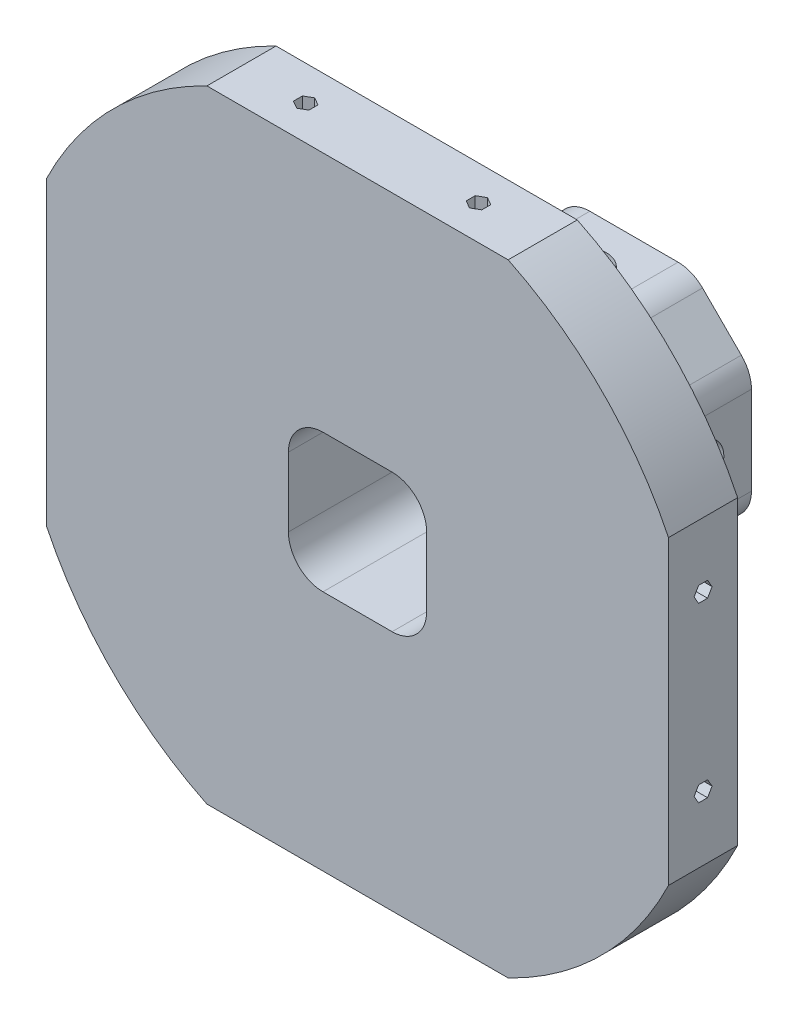
SolidWorks part; units mm, degrees
ref_plane "正面" through (0, 0, 0) normal (0, 0, 1) x (1, 0, 0)
ref_plane "平面" through (0, 0, 0) normal (0, 1, 0) x (1, 0, 0)
ref_plane "右側面" through (0, 0, 0) normal (1, 0, 0) x (0, 0, -1)
sketch "ｽｹｯﾁ1" plane through (0, 0, 0) normal (0, 0, 1) x (1, 0, 0)
  line L0 (7.4558, -18) -> (18, -7.4558)
  line L1 (-18, 7.4558) -> (-18, -7.4558)
  line L2 (-18, -7.4558) -> (-7.4558, -18)
  line L3 (-7.4558, -18) -> (7.4558, -18)
  line L4 (18, -7.4558) -> (18, 7.4558)
  line L5 (18, 7.4558) -> (7.4558, 18)
  line L6 (7.4558, 18) -> (-7.4558, 18)
  line L7 (-7.4558, 18) -> (-18, 7.4558)
  circle A0 centre (0, 0) radius 18 construction
  point P1 (0, -18)
  point P12 (-18, 0)
  dimension "D1" = 18
extrude "ﾎﾞｽ - 押し出し1" add sketch "ｽｹｯﾁ1" along normal mid plane 15
sketch "ｽｹｯﾁ2" plane through (0, 0, 7.5) normal (0, 0, 1) x (1, 0, 0)
  line L0 (7.4558, 18) -> (-7.4558, 18) construction
  line L1 (10, -10) -> (-10, -10)
  line L2 (10, -10) -> (10, 10)
  line L3 (10, 10) -> (-10, 10)
  line L4 (-10, -10) -> (-10, 10)
  line L5 (10, -10) -> (-10, 10) construction
  line L6 (10, 10) -> (-10, -10) construction
  line L7 (18, -7.4558) -> (18, 7.4558) construction
  point P0 (0, 0)
  dimension "D1" = 8
  dimension "D2" = 8
extrude "ｶｯﾄ - 押し出し1" cut sketch "ｽｹｯﾁ2" against normal through all both and the other way through all
sketch "ｽｹｯﾁ11" plane through (0, 18, 0) normal (0, 1, 0) x (1, 0, 0)
  line L1 (-14.7524, -23.747) -> (14.7524, -23.747)
  line L2 (-14.7524, -23.747) -> (-14.7524, 23.747)
  line L3 (-14.7524, 23.747) -> (14.7524, 23.747)
  line L4 (14.7524, -23.747) -> (14.7524, 23.747)
  line L5 (-14.7524, -23.747) -> (14.7524, 23.747) construction
  line L6 (-14.7524, 23.747) -> (14.7524, -23.747) construction
  point P0 (0, 0)
extrude "ｶｯﾄ - 押し出し7" cut sketch "ｽｹｯﾁ11" against normal blind 1
mirror "ﾐﾗｰ1" about plane through (0, 0, 0) normal (0, 1, 0) of "ｶｯﾄ - 押し出し7"
sketch "ｽｹｯﾁ12" plane through (-18, 0, 0) normal (-1, 0, 0) x (0, 0, 1)
  line L1 (-10.119, -12.8597) -> (10.119, -12.8597)
  line L2 (-10.119, -12.8597) -> (-10.119, 12.8597)
  line L3 (-10.119, 12.8597) -> (10.119, 12.8597)
  line L4 (10.119, -12.8597) -> (10.119, 12.8597)
  line L5 (-10.119, -12.8597) -> (10.119, 12.8597) construction
  line L6 (-10.119, 12.8597) -> (10.119, -12.8597) construction
  point P0 (0, 0)
extrude "ｶｯﾄ - 押し出し8" cut sketch "ｽｹｯﾁ12" against normal blind 1
mirror "ﾐﾗｰ2" about plane through (0, 0, 0) normal (1, 0, 0) of "ｶｯﾄ - 押し出し8"
fillet "ﾌｨﾚｯﾄ1" radius 5 4 edges at (10, -10, 0) (-10, -10, 0) (10, 10, 0) (-10, 10, 0)
fillet "ﾌｨﾚｯﾄ2" radius 5 8 edges at (17, -8.4558, 0) (8.4558, -17, 0) (-8.4558, -17, 0) (17, 8.4558, 0) (-17, -8.4558, 0) (-17, 8.4558, 0) (8.4558, 17, 0) (-8.4558, 17, 0)
sketch "ｽｹｯﾁ3" plane through (0, -17, 0) normal (0, -1, 0) x (1, 0, 0)
  circle A0 centre (0, 0) radius 4.2
  dimension "D1" = 8.4
extrude "ｶｯﾄ - 押し出し2" cut sketch "ｽｹｯﾁ3" against normal through all both and the other way through all
sketch "ｽｹｯﾁ4" plane through (17, 0, 0) normal (1, 0, 0) x (0, 0, -1)
  circle A0 centre (0, 0) radius 4.2
  dimension "D1" = 8.4
extrude "ｶｯﾄ - 押し出し3" cut sketch "ｽｹｯﾁ4" against normal through all both and the other way through all
sketch "ｽｹｯﾁ5" plane through (0, 0, 7.5) normal (0, 0, 1) x (1, 0, 0)
  line L0 (5, 10) -> (-5, 10) construction
  line L1 (10, -5) -> (10, 5) construction
  line L2 (-5, -10) -> (5, -10) construction
  line L3 (-10, 5) -> (-10, -5) construction
  line L4 (5, 10) -> (-5, 10)
  line L5 (10, -5) -> (10, 5)
  line L6 (-5, -10) -> (5, -10)
  line L7 (-10, 5) -> (-10, -5)
  line L8 (9.9203, -15.5355) -> (15.5355, -9.9203)
  line L9 (17, -6.3848) -> (17, 6.3848)
  line L10 (15.5355, 9.9203) -> (9.9203, 15.5355)
  line L11 (17, -6.3848) -> (17, 6.3848)
  line L12 (-9.9203, 15.5355) -> (-15.5355, 9.9203)
  line L13 (6.3848, 17) -> (-6.3848, 17)
  line L14 (-15.5355, -9.9203) -> (-9.9203, -15.5355)
  line L15 (6.3848, 17) -> (-6.3848, 17)
  line L16 (9.9203, -15.5355) -> (15.5355, -9.9203)
  line L18 (15.5355, 9.9203) -> (9.9203, 15.5355)
  line L20 (-9.9203, 15.5355) -> (-15.5355, 9.9203)
  line L22 (-15.5355, -9.9203) -> (-9.9203, -15.5355)
  line L32 (-17, 6.3848) -> (-17, -6.3848)
  line L33 (-17, 6.3848) -> (-17, -6.3848)
  line L34 (-6.3848, -17) -> (6.3848, -17)
  line L35 (-6.3848, -17) -> (6.3848, -17)
  arc A0 (-5, 10) -> (-10, 5) centre (-5, 5) ccw construction
  arc A1 (-5, 10) -> (-10, 5) centre (-5, 5) ccw
  arc A2 (10, 5) -> (5, 10) centre (5, 5) ccw construction
  arc A3 (5, -10) -> (10, -5) centre (5, -5) ccw construction
  arc A4 (-10, -5) -> (-5, -10) centre (-5, -5) ccw construction
  arc A5 (10, 5) -> (5, 10) centre (5, 5) ccw
  arc A6 (5, -10) -> (10, -5) centre (5, -5) ccw
  arc A7 (-10, -5) -> (-5, -10) centre (-5, -5) ccw
  arc A24 (15.5355, -9.9203) -> (17, -6.3848) centre (12, -6.3848) ccw
  arc A25 (15.5355, -9.9203) -> (17, -6.3848) centre (12, -6.3848) ccw
  arc A26 (17, 6.3848) -> (15.5355, 9.9203) centre (12, 6.3848) ccw
  arc A27 (17, 6.3848) -> (15.5355, 9.9203) centre (12, 6.3848) ccw
  arc A28 (9.9203, 15.5355) -> (6.3848, 17) centre (6.3848, 12) ccw
  arc A29 (9.9203, 15.5355) -> (6.3848, 17) centre (6.3848, 12) ccw
  arc A30 (-6.3848, 17) -> (-9.9203, 15.5355) centre (-6.3848, 12) ccw
  arc A31 (-6.3848, 17) -> (-9.9203, 15.5355) centre (-6.3848, 12) ccw
  arc A32 (-15.5355, 9.9203) -> (-17, 6.3848) centre (-12, 6.3848) ccw
  arc A33 (-15.5355, 9.9203) -> (-17, 6.3848) centre (-12, 6.3848) ccw
  arc A34 (-17, -6.3848) -> (-15.5355, -9.9203) centre (-12, -6.3848) ccw
  arc A35 (-17, -6.3848) -> (-15.5355, -9.9203) centre (-12, -6.3848) ccw
  arc A36 (-9.9203, -15.5355) -> (-6.3848, -17) centre (-6.3848, -12) ccw
  arc A37 (-9.9203, -15.5355) -> (-6.3848, -17) centre (-6.3848, -12) ccw
  arc A38 (6.3848, -17) -> (9.9203, -15.5355) centre (6.3848, -12) ccw
  arc A39 (6.3848, -17) -> (9.9203, -15.5355) centre (6.3848, -12) ccw
  dimension "D1" = 0
extrude "ﾎﾞｽ - 押し出し2" add sketch "ｽｹｯﾁ5" along normal blind 15
sketch "ｽｹｯﾁ6" plane through (0, -17, 0) normal (0, -1, 0) x (1, 0, 0)
  circle A1 centre (0, 0) radius 4.2
  circle A2 centre (0, 0) radius 3.5
  circle A3 centre (0, 0) radius 4.2 construction
  dimension "D1" = 7
extrude "ﾎﾞｽ - 押し出し3" add sketch "ｽｹｯﾁ6" against normal blind 3.4
mirror "ﾐﾗｰ3" about plane through (0, 0, 0) normal (0, 1, 0) of "ﾎﾞｽ - 押し出し3"
sketch "ｽｹｯﾁ13" plane through (-17, 0, 0) normal (-1, 0, 0) x (0, 0, 1)
  circle A0 centre (0, 0) radius 4.2 construction
  circle A1 centre (0, 0) radius 4.2
  circle A2 centre (0, 0) radius 3.5
  dimension "D1" = 7
extrude "ﾎﾞｽ - 押し出し4" add sketch "ｽｹｯﾁ13" along direction (-1, 0, 0) on the side against the normal blind 3.4
mirror "ﾐﾗｰ4" about plane through (0, 0, 0) normal (1, 0, 0) of "ﾎﾞｽ - 押し出し4"
sketch "ｽｹｯﾁ14" plane through (0, 0, 22.5) normal (0, 0, 1) x (1, 0, 0)
  line L0 (-5, -10) -> (5, -10) construction
  line L1 (10, -5) -> (10, 5) construction
  line L2 (-10, 5) -> (-10, -5) construction
  line L3 (5, 10) -> (-5, 10) construction
  line L4 (-5, -10) -> (5, -10)
  line L5 (10, -5) -> (10, 5)
  line L6 (-10, 5) -> (-10, -5)
  line L7 (5, 10) -> (-5, 10)
  circle A0 centre (0, 0) radius 50
  arc A1 (5, -10) -> (10, -5) centre (5, -5) ccw construction
  arc A2 (-10, -5) -> (-5, -10) centre (-5, -5) ccw construction
  arc A3 (-5, 10) -> (-10, 5) centre (-5, 5) ccw construction
  arc A4 (10, 5) -> (5, 10) centre (5, 5) ccw construction
  arc A5 (5, -10) -> (10, -5) centre (5, -5) ccw
  arc A6 (-10, -5) -> (-5, -10) centre (-5, -5) ccw
  arc A7 (-5, 10) -> (-10, 5) centre (-5, 5) ccw
  arc A8 (10, 5) -> (5, 10) centre (5, 5) ccw
  dimension "D1" = 100
extrude "ﾎﾞｽ - 押し出し5" add sketch "ｽｹｯﾁ14" along normal blind 10
sketch "ｽｹｯﾁ15" plane through (0, 0, 32.5) normal (0, 0, 1) x (1, 0, 0)
  line L1 (-45, -45) -> (45, -45)
  line L2 (-45, -45) -> (-45, 45)
  line L3 (-45, 45) -> (45, 45)
  line L4 (45, -45) -> (45, 45)
  line L5 (-45, -45) -> (45, 45) construction
  line L6 (-45, 45) -> (45, -45) construction
  line L7 (-79.0589, -87.0161) -> (79.0589, -87.0161)
  line L8 (-79.0589, -87.0161) -> (-79.0589, 87.0161)
  line L9 (-79.0589, 87.0161) -> (79.0589, 87.0161)
  line L10 (79.0589, -87.0161) -> (79.0589, 87.0161)
  line L11 (-79.0589, -87.0161) -> (79.0589, 87.0161) construction
  line L12 (-79.0589, 87.0161) -> (79.0589, -87.0161) construction
  point P0 (0, 0)
  point P6 (0, 0)
  circle M9 centre (0, 0) radius 50
  dimension "D1" = 90
extrude "ｶｯﾄ - 押し出し9" cut sketch "ｽｹｯﾁ15" against normal blind 10 contours L3 M9 | L4 M9 | L1 M9 | L2 M9
chamfer "面取り1" distance 5 angle 45 16 edges at (17, 0, 22.5) (16.6194, 8.2982, 22.5) (16.6194, -8.2982, 22.5) (12.7279, 12.7279, 22.5) (12.7279, -12.7279, 22.5) (8.2982, 16.6194, 22.5) (8.2982, -16.6194, 22.5) (0, 17, 22.5) (0, -17, 22.5) (-8.2982, 16.6194, 22.5) (-8.2982, -16.6194, 22.5) (-12.7279, 12.7279, 22.5) (-12.7279, -12.7279, 22.5) (-16.6194, 8.2982, 22.5) (-16.6194, -8.2982, 22.5) (-17, 0, 22.5)
sketch "ｽｹｯﾁ16" plane through (-45, 0, 0) normal (-1, 0, 0) x (0, 0, 1)
  line L0 (32.5, -21.7945) -> (32.5, 21.7945) construction
  line L1 (28.8, 12.5) -> (28.15, 13.6258)
  line L2 (28.15, 13.6258) -> (26.85, 13.6258)
  line L3 (26.85, 13.6258) -> (26.2, 12.5)
  line L4 (26.2, 12.5) -> (26.85, 11.3742)
  line L5 (26.85, 11.3742) -> (28.15, 11.3742)
  line L6 (28.15, 11.3742) -> (28.8, 12.5)
  line L7 (28.8, -12.5) -> (28.15, -11.3742)
  line L8 (28.15, -11.3742) -> (26.85, -11.3742)
  line L9 (26.85, -11.3742) -> (26.2, -12.5)
  line L10 (26.2, -12.5) -> (26.85, -13.6258)
  line L11 (26.85, -13.6258) -> (28.15, -13.6258)
  line L12 (28.15, -13.6258) -> (28.8, -12.5)
  line L13 (22.5, 21.7945) -> (32.5, 21.7945) construction
  circle A0 centre (27.5, 12.5) radius 1.1258 construction
  circle A1 centre (27.5, -12.5) radius 1.1258 construction
  point P9 (0, 0)
  point P19 (32.5, 0)
  point P22 (27.5, 21.7945)
  point P23 (0, 0)
  point P24 (0, 0)
  dimension "D1" = 2.6
  dimension "D2" = 25
  dimension "D3" = 12.5
extrude "ｶｯﾄ - 押し出し10" cut sketch "ｽｹｯﾁ16" against normal blind 15
sketch "ｽｹｯﾁ17" plane through (0, 0, 0) normal (0, 1, 0) x (1, 0, 0)
  line L0 (0, -40.0648) -> (0, 12.9972)
pattern_circular "円形ﾊﾟﾀｰﾝ1" count 4 over 360 about axis through (0, 0, 0) along (0, 0, 1) of "ｶｯﾄ - 押し出し10"
equation "\"D3@ｽｹｯﾁ16\"=\"D2@ｽｹｯﾁ16\"/2"
